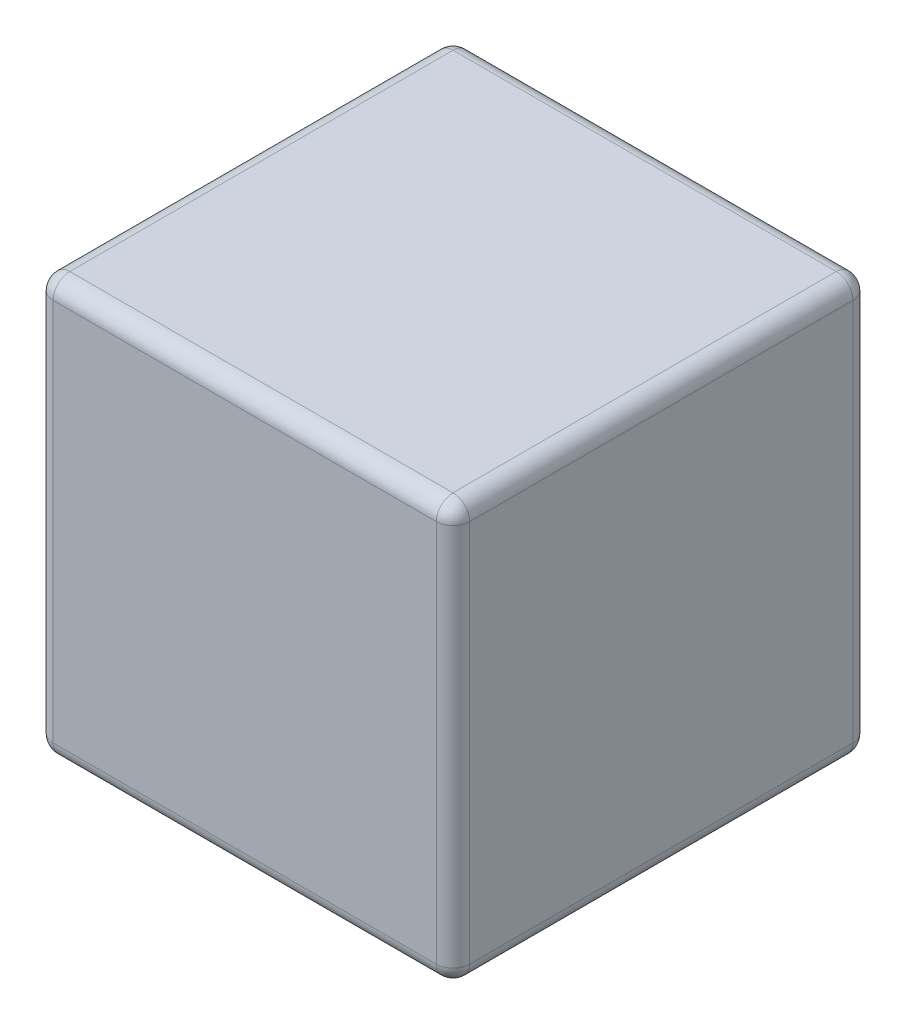
SolidWorks part; units mm, degrees
ref_plane "Front Plane" through (0, 0, 0) normal (0, 0, 1) x (1, 0, 0)
ref_plane "Top Plane" through (0, 0, 0) normal (0, 1, 0) x (1, 0, 0)
ref_plane "Right Plane" through (0, 0, 0) normal (1, 0, 0) x (0, 0, -1)
sketch "Sketch1" plane through (0, 0, 0) normal (0, 1, 0) x (1, 0, 0)
  line L1 (-125, -125) -> (125, -125)
  line L2 (-125, -125) -> (-125, 125)
  line L3 (-125, 125) -> (125, 125)
  line L4 (125, -125) -> (125, 125)
  line L5 (-125, -125) -> (125, 125) construction
  line L6 (-125, 125) -> (125, -125) construction
  point P0 (0, 0)
  dimension "D1" = 250
  dimension "D2" = 250
extrude "Boss-Extrude1" add sketch "Sketch1" along normal mid plane 250
fillet "Fillet1" radius 10 12 edges at (-125, 0, -125) (0, -125, -125) (-125, -125, 0) (125, 0, -125) (125, -125, 0) (-125, 0, 125) (125, 0, 125) (0, -125, 125) (0, 125, 125) (-125, 125, 0) (0, 125, -125) (125, 125, 0)
sketch "Sketch2" plane through (0, 0, -125) normal (0, 0, -1) x (-1, 0, 0)
  text T0 "LIFE SUPPORT" font "Century Gothic" height 25
  point P1 (-96.417, 56.2612)
extrude "Cut-Extrude1" cut sketch "Sketch2" against normal blind 5
